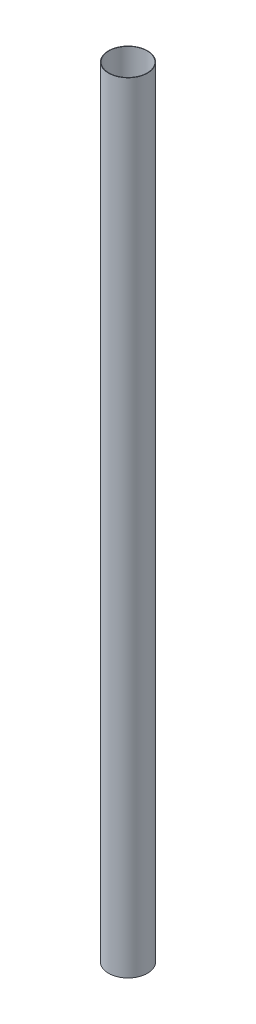
SolidWorks part; units mm, degrees
ref_plane "前基準面" through (0, 0, 0) normal (0, 0, 1) x (1, 0, 0)
ref_plane "上基準面" through (0, 0, 0) normal (0, 1, 0) x (1, 0, 0)
ref_plane "右基準面" through (0, 0, 0) normal (1, 0, 0) x (0, 0, -1)
sketch "草圖1" plane through (0, 0, 0) normal (0, 1, 0) x (1, 0, 0)
  circle A0 centre (0, 0) radius 2.5
  circle A1 centre (0, 0) radius 2.45
  dimension "D1" = 5
  dimension "D2" = 0.05
extrude "填料-伸長1" add sketch "草圖1" along normal blind 100
